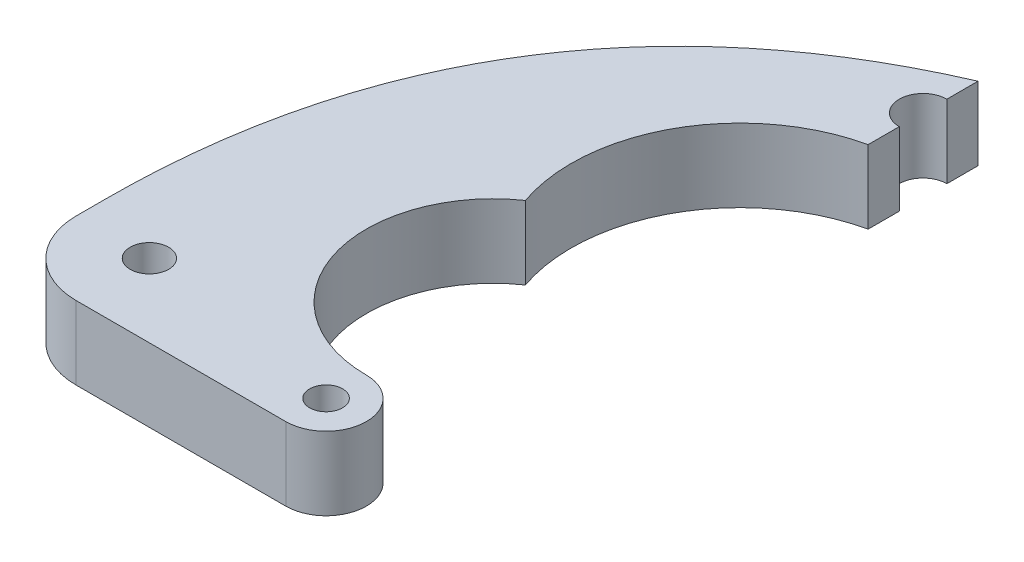
SolidWorks part; units mm, degrees
ref_plane "Front Plane" through (0, 0, 0) normal (0, 0, 1) x (1, 0, 0)
ref_plane "Top Plane" through (0, 0, 0) normal (0, 1, 0) x (1, 0, 0)
ref_plane "Right Plane" through (0, 0, 0) normal (1, 0, 0) x (0, 0, -1)
sketch "Sketch1" plane through (0, 0, 0) normal (0, 1, 0) x (1, 0, 0)
  line L8 (0, 51.3) -> (0, 53)
  line L9 (-18.25, 23.6) -> (-18.25, 22)
  line L10 (-14.25, 18) -> (-2.8, 18)
  line L11 (0, 47) -> (0, 48.7)
  circle A1 centre (-2.8, 20.2) radius 0.9
  circle A3 centre (-14.25, 22) radius 1.05
  arc A10 (0, 51.3) -> (0, 48.7) centre (0, 50) ccw
  arc A11 (-18.25, 22) -> (-14.25, 18) centre (-14.25, 22) ccw
  arc A12 (-2.8, 18) -> (-2.8, 22.4) centre (-2.8, 20.2) ccw
  arc A13 (-6.7178, 35) -> (-2.8, 22.4) centre (-2.8, 29.3091) ccw
  arc A14 (0, 47) -> (-6.7178, 35) centre (2, 38) ccw
  spline S2 degree 3 poles (0, 53) (-11.2886, 48.1071) (-18.25, 38.6913) (-18.25, 23.6) knots 0 0 0 0 1 1 1 1
  dimension "D1" = 1.8
  dimension "D2" = 2.1
  dimension "D3" = 1.3
  dimension "D4" = 4
  dimension "D5" = 2.2
  dimension "D6" = 6.9091
  dimension "D7" = 9.2195
  dimension "D8" = 2
  dimension "D9" = 2.8
  dimension "D10" = 6.7178
  dimension "D11" = 18.25
  dimension "D12" = 18
  dimension "D13" = 50
  dimension "D14" = 23.6
extrude "Boss-Extrude2" add sketch "Sketch1" along normal blind 4 contours L10 A12 A13 A14 L11 A10 L8 S2 L9 A11
